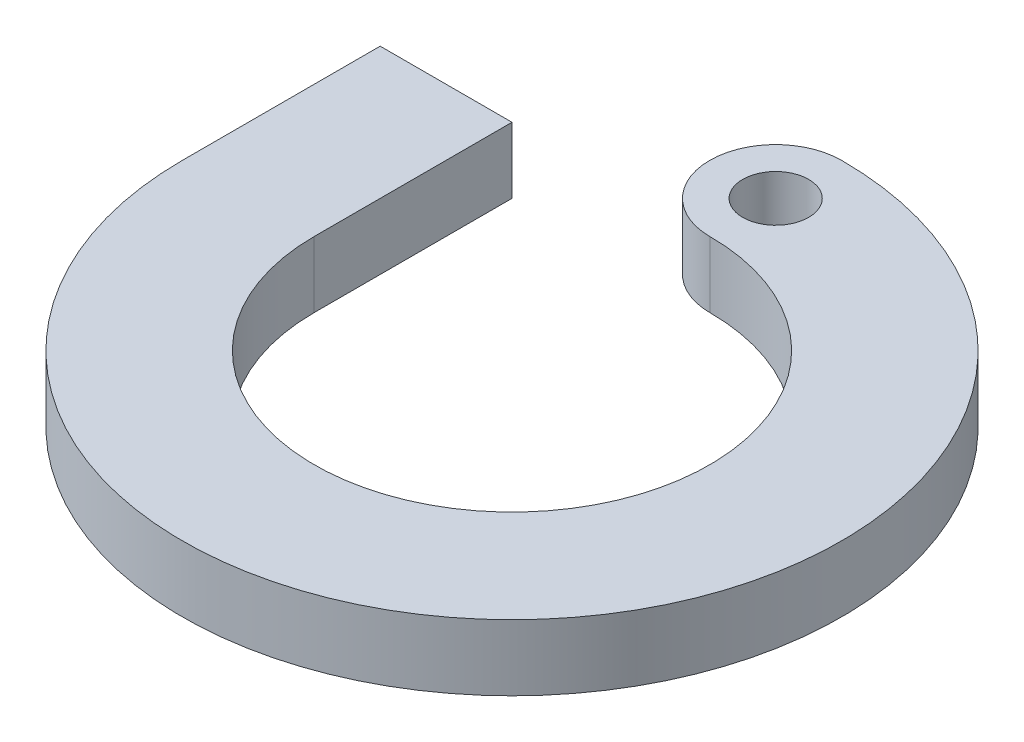
SolidWorks part; units mm, degrees
ref_plane "前视基准面" through (0, 0, 0) normal (0, 0, 1) x (1, 0, 0)
ref_plane "上视基准面" through (0, 0, 0) normal (0, 1, 0) x (1, 0, 0)
ref_plane "右视基准面" through (0, 0, 0) normal (1, 0, 0) x (0, 0, -1)
other "Configuration Table"
sketch "草图1" plane through (0, 0, 0) normal (0, 1, 0) x (1, 0, 0)
  line L4 (-50, 0) -> (-50, 30)
  line L5 (-50, 30) -> (-30, 30)
  line L6 (-30, 0) -> (-30, 30)
  arc A0 (-50, 0) -> (0, 50) centre (0, 0) ccw
  arc A1 (-30, 0) -> (0, 30) centre (0, 0) ccw
  arc A2 (0, 50) -> (0, 30) centre (0, 40) ccw
  circle A3 centre (0, 40) radius 5
  dimension "D1" = 30
  dimension "D2" = 50
  dimension "D3" = 20
  dimension "D4" = 30
extrude "凸台-拉伸1" add sketch "草图1" along normal blind 10
